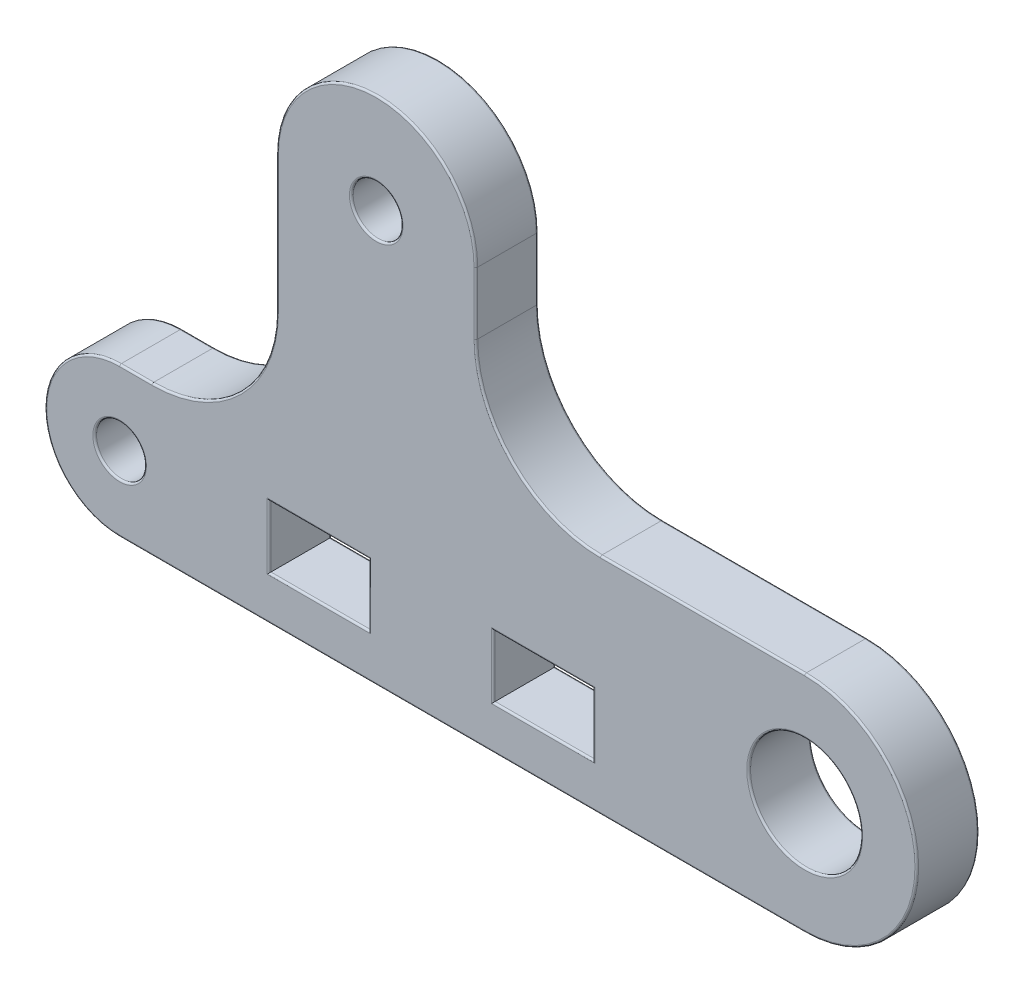
SolidWorks part; units mm, degrees
ref_plane "前视基准面" through (0, 0, 0) normal (0, 0, 1) x (1, 0, 0)
ref_plane "上视基准面" through (0, 0, 0) normal (0, 1, 0) x (1, 0, 0)
ref_plane "右视基准面" through (0, 0, 0) normal (1, 0, 0) x (0, 0, -1)
sketch "草图1" plane through (0, 0, 0) normal (0, 0, 1) x (1, 0, 0)
  line L0 (-27.5, 0) -> (27.5, 0)
  line L1 (-27.5, 12) -> (-24.9, 12)
  line L2 (-14.9, 22) -> (-14.9, 33)
  line L3 (27.5, 18) -> (11.1, 18)
  line L4 (1.1, 28) -> (1.1, 33)
  line L5 (-27.5, 6) -> (-15.5, 6) construction
  line L7 (-15.5, 8.5) -> (-7.5, 8.5)
  line L8 (-15.5, 8.5) -> (-15.5, 3.5)
  line L9 (-15.5, 3.5) -> (-7.5, 3.5)
  line L10 (-7.5, 8.5) -> (-7.5, 3.5)
  line L11 (2.5, 8.5) -> (10.5, 8.5)
  line L12 (2.5, 8.5) -> (2.5, 3.5)
  line L13 (2.5, 3.5) -> (10.5, 3.5)
  line L14 (10.5, 8.5) -> (10.5, 3.5)
  arc A0 (27.5, 0) -> (27.5, 18) centre (27.5, 9) ccw
  arc A1 (-27.5, 0) -> (-27.5, 12) centre (-27.5, 6) cw
  circle A2 centre (27.5, 9) radius 4.5
  circle A3 centre (-27.5, 6) radius 2
  circle A4 centre (-6.9, 33) radius 2
  circle A5 centre (-6.9, 33) radius 8 construction
  arc A6 (-14.9, 33) -> (1.1, 33) centre (-6.9, 33) cw
  arc A7 (11.1, 18) -> (1.1, 28) centre (11.1, 28) cw
  arc A8 (-24.9, 12) -> (-14.9, 22) centre (-24.9, 22) ccw
  dimension "D2" = 9
  dimension "D3" = 6
  dimension "D4" = 4
  dimension "D5" = 9
  dimension "D7" = 6.9
  dimension "D8" = 16
  dimension "D9" = 10
  dimension "D1" = 55
  dimension "D6" = 33
  dimension "D10" = 12
  dimension "D11" = 8
  dimension "D12" = 5
  dimension "D13" = 10
extrude "凸台-拉伸1" add sketch "草图1" along normal mid plane 5
fillet "圆角1" radius 0.15 42 edges at (6.5, 3.5, 2.5) (10.5, 6, 2.5) (6.5, 8.5, 2.5) (2.5, 6, 2.5) (-4.9, 33, 2.5) (-25.5, 6, 2.5) (32, 9, 2.5) (-26.2, 12, 2.5) (-17.8289, 14.9289, 2.5) (-14.9, 27.5, 2.5) (-6.9, 41, 2.5) (1.1, 30.5, 2.5) (4.0289, 20.9289, 2.5) (19.3, 18, 2.5) (36.5, 9, 2.5) (0, 0, 2.5) (-33.5, 6, 2.5) (-11.5, 3.5, 2.5) (-7.5, 6, 2.5) (-11.5, 8.5, 2.5) (-15.5, 6, 2.5) (10.5, 6, -2.5) (6.5, 3.5, -2.5) (2.5, 6, -2.5) (6.5, 8.5, -2.5) (-7.5, 6, -2.5) (-11.5, 3.5, -2.5) (-15.5, 6, -2.5) (-11.5, 8.5, -2.5) (-4.9, 33, -2.5) (32, 9, -2.5) (0, 0, -2.5) (36.5, 9, -2.5) (19.3, 18, -2.5) (4.0289, 20.9289, -2.5) (1.1, 30.5, -2.5) (-6.9, 41, -2.5) (-14.9, 27.5, -2.5) (-17.8289, 14.9289, -2.5) (-26.2, 12, -2.5) (-33.5, 6, -2.5) (-25.5, 6, -2.5)
